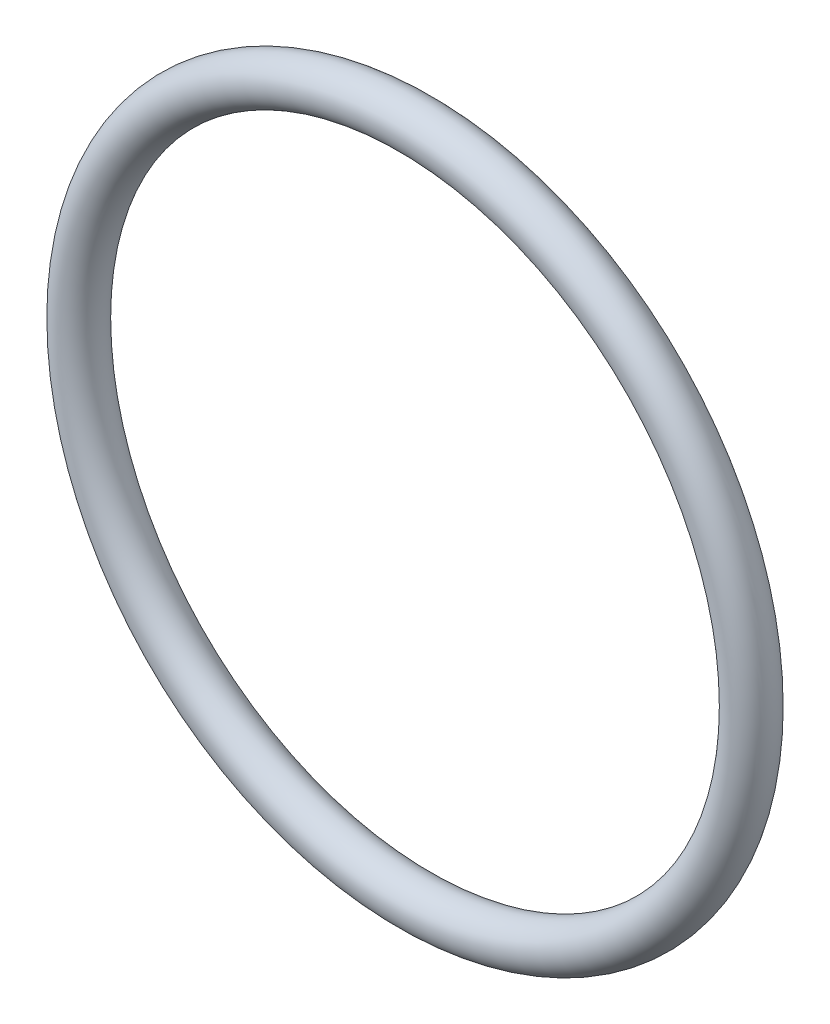
SolidWorks part; units mm, degrees
material "橡胶"
ref_plane "前视基准面" through (0, 0, 0) normal (0, 0, 1) x (1, 0, 0)
ref_plane "上视基准面" through (0, 0, 0) normal (0, 1, 0) x (1, 0, 0)
ref_plane "右视基准面" through (0, 0, 0) normal (1, 0, 0) x (0, 0, -1)
sketch "草图1" plane through (0, 0, 0) normal (1, 0, 0) x (0, 0, -1)
  line L0 (0, 0) -> (0, 13.4)
  line L1 (-15.0261, 0) -> (17.2482, 0)
  circle A0 centre (0, 13.4) radius 0.9
revolve "旋转2" add sketch "草图1" angle 360 about L1
